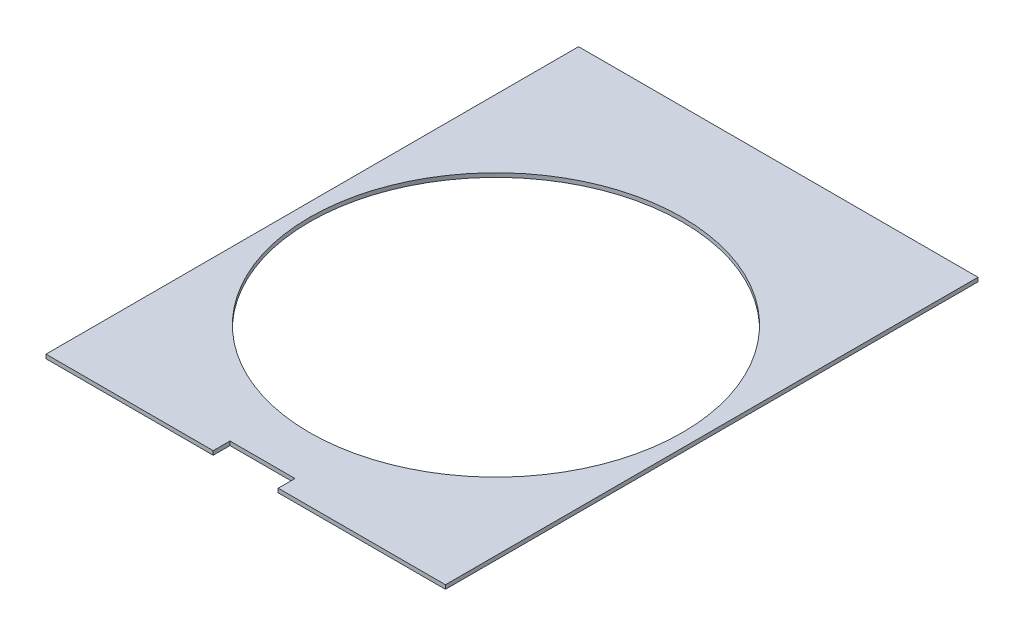
SolidWorks part; units mm, degrees
ref_plane "Front Plane" through (0, 0, 0) normal (0, 0, 1) x (1, 0, 0)
ref_plane "Top Plane" through (0, 0, 0) normal (0, 1, 0) x (1, 0, 0)
ref_plane "Right Plane" through (0, 0, 0) normal (1, 0, 0) x (0, 0, -1)
sketch "Sketch4" plane through (190.4633, 0, 436.2735) normal (0, 1, 0) x (1, 0, 0)
  line L1 (-190.5, -254) -> (190.5, -254)
  line L2 (-190.5, -254) -> (-190.5, 254)
  line L3 (-190.5, 254) -> (190.5, 254)
  line L4 (190.5, -254) -> (190.5, 254)
  line L5 (-190.5, -254) -> (190.5, 254) construction
  line L6 (-190.5, 254) -> (190.5, -254) construction
  point P0 (0, 0)
extrude "Boss-Extrude1" add sketch "Sketch4" along normal blind 3.81
sketch "Sketch5" plane through (0, 3.81, 0) normal (0, 1, 0) x (1, 0, 0)
  line L0 (190.4633, -690.2735) -> (190.4633, -451.5834) construction
  line L1 (-0.0367, -690.2735) -> (380.9633, -690.2735) construction
  circle A0 centre (190.4633, -451.5834) radius 177.8
  dimension "D1" = 355.6
extrude "Cut-Extrude1" cut sketch "Sketch5" against normal through all
sketch "Sketch6" plane through (0, 3.81, 0) normal (0, 1, 0) x (1, 0, 0)
  line L0 (-0.0367, -690.2735) -> (380.9633, -690.2735) construction
  line L2 (159.4633, -690.2735) -> (221.4633, -690.2735)
  line L3 (159.4633, -690.2735) -> (159.4633, -674.2735)
  line L4 (159.4633, -674.2735) -> (221.4633, -674.2735)
  line L5 (221.4633, -690.2735) -> (221.4633, -674.2735)
  point P3 (190.4633, -690.2735)
  dimension "D1" = 62
  dimension "D2" = 16
extrude "Cut-Extrude2" cut sketch "Sketch6" against normal through all
